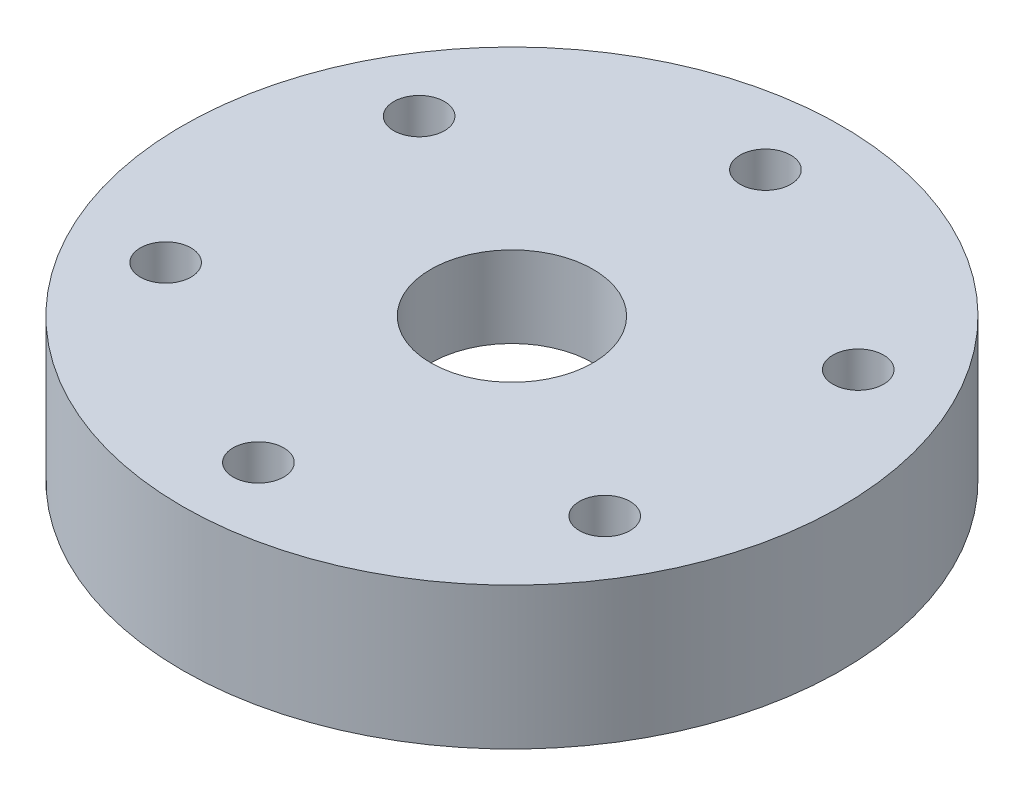
SolidWorks part; units mm, degrees
ref_plane "Front Plane" through (0, 0, 0) normal (0, 0, 1) x (1, 0, 0)
ref_plane "Top Plane" through (0, 0, 0) normal (0, 1, 0) x (1, 0, 0)
ref_plane "Right Plane" through (0, 0, 0) normal (1, 0, 0) x (0, 0, -1)
sketch "Sketch1" plane through (0, 0, 0) normal (0, 0, 1) x (1, 0, 0)
  line L0 (0, 16.7086) -> (0, -15.5104) construction
  line L1 (-8, 4.2145) -> (-32.5, 4.2145)
  line L2 (-32.5, 4.2145) -> (-32.5, -9.7855)
  line L3 (-32.5, -9.7855) -> (-17.5, -9.7855)
  line L4 (-17.5, -9.7855) -> (-17.5, -3.7855)
  line L5 (-17.5, -3.7855) -> (-8, -3.7855)
  line L7 (-8, 4.2145) -> (-8, -3.7855)
  dimension "D1" = 65
  dimension "D2" = 35
  dimension "D3" = 16
  dimension "D4" = 6
  dimension "D5" = 8
revolve "Revolve1" add sketch "Sketch1" angle 360 about L0
sketch "Sketch2" plane through (0, -9.7855, 0) normal (0, -1, 0) x (1, 0, 0)
  circle A0 centre (0, 0) radius 25 construction
  circle A2 centre (0, 0) radius 17.5 construction
  circle A4 centre (0, 25) radius 2.5
  circle A5 centre (21.6506, 12.5) radius 2.5
  circle A6 centre (21.6506, -12.5) radius 2.5
  circle A7 centre (0, -25) radius 2.5
  circle A8 centre (-21.6506, -12.5) radius 2.5
  circle A9 centre (-21.6506, 12.5) radius 2.5
  point P19 (0, 0)
  dimension "D1" = 7.5
  dimension "D2" = 5
  dimension "D3" = 6
extrude "Cut-Extrude1" cut sketch "Sketch2" against normal blind 23
